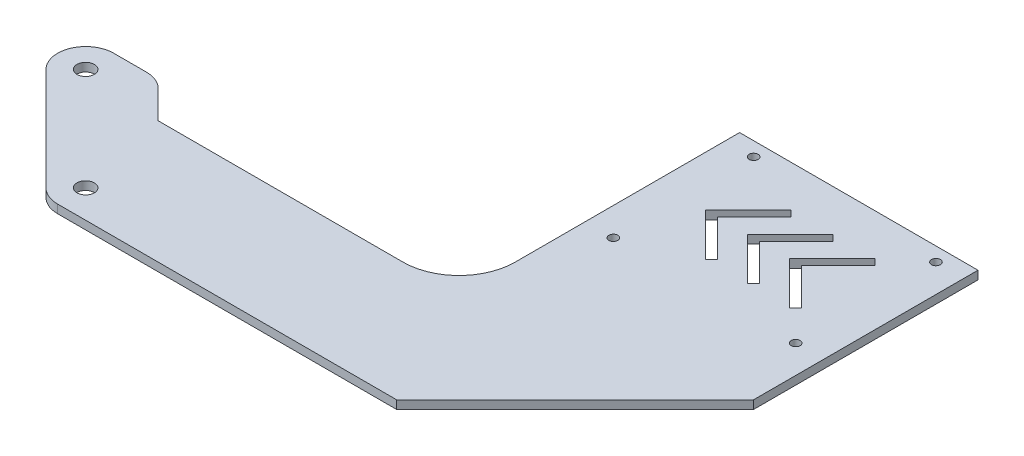
SolidWorks part; units mm, degrees
material "Thornel Mat VMA"
ref_plane "前视基准面" through (0, 0, 0) normal (0, 0, 1) x (1, 0, 0)
ref_plane "上视基准面" through (0, 0, 0) normal (0, 1, 0) x (1, 0, 0)
ref_plane "右视基准面" through (0, 0, 0) normal (1, 0, 0) x (0, 0, -1)
sketch "草图1" plane through (0, 0, 0) normal (0, 1, 0) x (1, 0, 0)
  line L1 (0, 0) -> (65, 0) construction
  line L2 (0, 0) -> (0, 50) construction
  line L3 (0, 50) -> (65, 50) construction
  line L4 (65, 0) -> (65, 50) construction
  line L5 (32.5, 50) -> (32.5, 0) construction
  line L6 (0, 25) -> (65, 25) construction
  line L7 (-10, -5) -> (75, -5)
  line L8 (-10, -5) -> (-10, 55)
  line L9 (-10, 55) -> (75, 55)
  line L10 (75, -5) -> (75, 55)
  line L11 (-10, -5) -> (75, 55) construction
  line L12 (-10, 55) -> (75, -5) construction
  circle A0 centre (0, 50) radius 1.6
  circle A1 centre (65, 50) radius 1.6
  circle A2 centre (65, 0) radius 1.6
  circle A3 centre (0, 0) radius 1.6
  point P8 (32.5, 25)
  point P568 (32.5, 25)
  dimension "D3" = 3.2
  dimension "D1" = 50
  dimension "D2" = 65
  dimension "D4" = 10
  dimension "D5" = 60
extrude "凸台-拉伸1" add sketch "草图1" along normal blind 3
sketch "草图2" plane through (0, 0, 0) normal (0, 1, 0) x (1, 0, 0)
  line L0 (75, -5) -> (75, 55) construction
  line L1 (-10, -5) -> (75, -5)
  line L2 (-10, -5) -> (-10, -45)
  line L3 (-10, -45) -> (75, -45) construction
  line L4 (75, -5) -> (75, -25)
  line L5 (32.5, -45) -> (32.5, -5) construction
  line L6 (-10, -25) -> (75, -25) construction
  line L7 (-157.2792, -45) -> (-113.6396, -88.6396)
  line L8 (75, -25) -> (11.3604, -88.6396)
  line L9 (-58.1724, -88.6396) -> (11.3604, -88.6396)
  line L10 (-10, -45) -> (-117.2792, -45)
  line L11 (-157.2792, -45) -> (-170.2082, -32.0711)
  line L12 (-113.6396, -88.6396) -> (-58.1724, -88.6396)
  line L13 (-170.2082, -32.0711) -> (-130.2082, -32.0711)
  line L14 (-130.2082, -32.0711) -> (-117.2792, -45)
  point P912 (32.5, -25)
  dimension "D1" = 20
  dimension "D2" = 90
  dimension "D3" = 45
  dimension "D4" = 80
  dimension "D5" = 135
  dimension "D6" = 125
  dimension "D7" = 40
  dimension "D8" = 135
extrude "凸台-拉伸2" add sketch "草图2" along normal blind 3
fillet "圆角1" radius 20 1 edges at (-10, 1.5, 45)
fillet "圆角3" radius 10 3 edges at (-130.2082, 1.5, 32.0711) (-170.2082, 1.5, 32.0711) (-113.6396, 1.5, 88.6396)
sketch "草图4" plane through (0, 3, 0) normal (0, 1, 0) x (1, 0, 0)
  line L2 (-153.1371, -49.1421) -> (-116.5685, -85.7107) construction
  line L3 (-146.066, -42.0711) -> (-99.4975, -88.6396) construction
  line L4 (-109.4975, -88.6396) -> (11.3604, -88.6396) construction
  circle A0 centre (-146.066, -42.0711) radius 3.1
  circle A1 centre (-109.4975, -78.6396) radius 3.1
  dimension "D1" = 6.2
  dimension "D2" = 10
  dimension "D3" = 10
extrude "切除-拉伸1" cut sketch "草图4" against normal blind 10
sketch "草图5" plane through (0, 3, 0) normal (0, 1, 0) x (1, 0, 0)
  line L0 (0, 50) -> (65, 50) construction
  line L1 (65, 0) -> (65, 50) construction
  line L2 (0, 0) -> (65, 0) construction
  line L3 (0, 50) -> (0, 0) construction
  line L4 (0, 25) -> (65, 25) construction
  line L5 (10, 25) -> (24.1421, 39.1421)
  line L6 (10, 25) -> (24.1421, 10.8579)
  line L7 (25, 25) -> (39.1421, 39.1421)
  line L8 (25, 25) -> (39.1421, 10.8579)
  line L9 (40, 25) -> (54.1421, 39.1421)
  line L10 (40, 25) -> (54.1421, 10.8579)
  dimension "D1" = 45
  dimension "D2" = 20
  dimension "D3" = 10
  dimension "D4" = 3
extrude "切除-拉伸-薄壁1" cut sketch "草图5" against normal blind 10 thin thin type mid plane wall 3
